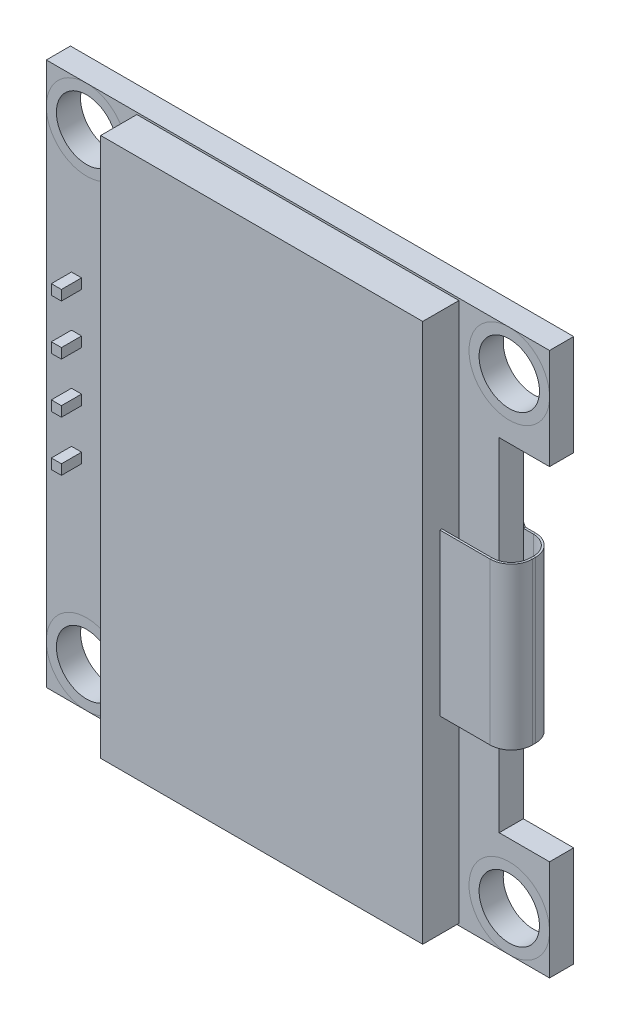
SolidWorks part; units mm, degrees
ref_plane "Front Plane" through (0, 0, 0) normal (0, 0, 1) x (1, 0, 0)
ref_plane "Top Plane" through (0, 0, 0) normal (0, 1, 0) x (1, 0, 0)
ref_plane "Right Plane" through (0, 0, 0) normal (1, 0, 0) x (0, 0, -1)
sketch "Sketch1" plane through (0, 0, 0) normal (0, 0, 1) x (1, 0, 0)
  line L0 (10, -8.5) -> (10, 8.5)
  line L1 (-12.5, -13.5) -> (12.5, -13.5)
  line L2 (-12.5, -13.5) -> (-12.5, 13.5)
  line L3 (-12.5, 13.5) -> (12.5, 13.5)
  line L4 (12.5, -13.5) -> (12.5, 13.5)
  line L5 (12.5, 13.5) -> (10, 13.5)
  line L6 (12.5, 13.5) -> (12.5, 8.5)
  line L7 (12.5, 8.5) -> (10, 8.5)
  line L8 (10, 13.5) -> (10, 8.5)
  line L9 (12.5, -13.5) -> (10, -13.5)
  line L10 (12.5, -13.5) -> (12.5, -8.5)
  line L11 (12.5, -8.5) -> (10, -8.5)
  line L12 (10, -13.5) -> (10, -8.5)
  dimension "D1" = 25
  dimension "D2" = 12.5
  dimension "D3" = 27
  dimension "D4" = 13.5
  dimension "D5" = 5
  dimension "D6" = 2.5
  dimension "D7" = 2.5
  dimension "D8" = 5
extrude "Boss-Extrude1" add sketch "Sketch1" along normal blind 1.2 contours L1 L12 L11 L4 L7 L8 L3 L2
sketch "Sketch2" plane through (0, 0, 1.2) normal (0, 0, 1) x (1, 0, 0)
  line L0 (12.5, 13.5) -> (12.5, 8.5) construction
  line L1 (-12.5, 13.5) -> (12.5, 13.5) construction
  line L2 (-1000, 0) -> (49000, 0) construction
  line L3 (0, -1000) -> (0, 49000) construction
  circle A0 centre (10.5, 11.5) radius 1.5
  circle A1 centre (10.5, -11.5) radius 1.5
  circle A2 centre (-10.5, 11.5) radius 1.5
  circle A3 centre (-10.5, -11.5) radius 1.5
  dimension "D1" = 3
  dimension "D2" = 2
  dimension "D3" = 2
extrude "Cut-Extrude1" cut sketch "Sketch2" against normal through all
sketch "Sketch3" plane through (0, 0, 1.2) normal (0, 0, 1) x (1, 0, 0)
  circle A0 centre (-10.5, 11.5) radius 2
  circle A1 centre (10.5, 11.5) radius 2
  circle A2 centre (10.5, -11.5) radius 2
  circle A3 centre (-10.5, -11.5) radius 2
split line "Split Line1"
sketch "Sketch5" plane through (0, 0, 0) normal (0, 0, -1) x (-1, 0, 0)
  line L0 (12.5, -11.5) -> (12.5, 11.5) construction
  line L1 (12.05, 6) -> (9.95, 6)
  line L2 (12.25, 5.8) -> (12.25, 3.7)
  line L4 (9.75, 5.8) -> (9.75, 3.7)
  line L5 (10.5, 13.5) -> (-10.5, 13.5) construction
  line L6 (12.25, 3.3) -> (12.25, 1.2)
  line L8 (9.75, 3.3) -> (9.75, 1.2)
  line L10 (12.25, 0.8) -> (12.25, -1.3)
  line L12 (9.75, 0.8) -> (9.75, -1.3)
  line L14 (12.25, -1.7) -> (12.25, -3.8)
  line L16 (9.75, -1.7) -> (9.75, -3.8)
  line L17 (12.05, -4) -> (9.95, -4)
  line L18 (12.05, 3.5) -> (9.95, 3.5) [skipped]
  line L19 (12.05, 1) -> (9.95, 1) [skipped]
  line L20 (12.05, -1.5) -> (9.95, -1.5) [skipped]
  arc A0 (9.95, 3.5) -> (9.75, 3.7) centre (9.95, 3.7) cw
  arc A1 (12.25, 3.7) -> (12.05, 3.5) centre (12.05, 3.7) cw
  arc A2 (12.05, 6) -> (12.25, 5.8) centre (12.05, 5.8) cw
  arc A3 (9.95, 6) -> (9.75, 5.8) centre (9.95, 5.8) ccw
  arc A4 (12.05, 3.5) -> (12.25, 3.3) centre (12.05, 3.3) cw
  arc A5 (12.25, 1.2) -> (12.05, 1) centre (12.05, 1.2) cw
  arc A6 (9.95, 3.5) -> (9.75, 3.3) centre (9.95, 3.3) ccw
  arc A7 (9.95, 1) -> (9.75, 1.2) centre (9.95, 1.2) cw
  arc A8 (12.05, 1) -> (12.25, 0.8) centre (12.05, 0.8) cw
  arc A9 (12.25, -1.3) -> (12.05, -1.5) centre (12.05, -1.3) cw
  arc A10 (9.95, 1) -> (9.75, 0.8) centre (9.95, 0.8) ccw
  arc A11 (9.95, -1.5) -> (9.75, -1.3) centre (9.95, -1.3) cw
  arc A12 (12.05, -1.5) -> (12.25, -1.7) centre (12.05, -1.7) cw
  arc A13 (12.25, -3.8) -> (12.05, -4) centre (12.05, -3.8) cw
  arc A14 (9.95, -1.5) -> (9.75, -1.7) centre (9.95, -1.7) ccw
  arc A15 (9.95, -4) -> (9.75, -3.8) centre (9.95, -3.8) cw
  point P12 (12.25, 3.5)
  point P15 (12.25, 6)
  point P18 (9.75, 6)
  dimension "D5" = 0.2
  dimension "D1" = 2.5
  dimension "D2" = 2.5
  dimension "D3" = 0.25
  dimension "D4" = 7.5
  dimension "D6" = 4
extrude "Boss-Extrude2" add sketch "Sketch5" along normal blind 2.5
sketch "Sketch6" plane through (0, 0, -2.5) normal (0, 0, -1) x (-1, 0, 0)
  line L0 (9.75, 5.8) -> (9.75, 3.7) construction
  line L1 (10.75, 5) -> (11.25, 5)
  line L2 (10.75, 5) -> (10.75, 4.5)
  line L3 (10.75, 4.5) -> (11.25, 4.5)
  line L4 (11.25, 5) -> (11.25, 4.5)
  line L5 (12.05, 6) -> (9.95, 6) construction
  line L6 (10.75, 2.5) -> (10.75, 2)
  line L7 (10.75, 2.5) -> (11.25, 2.5)
  line L8 (11.25, 2.5) -> (11.25, 2)
  line L9 (10.75, 2) -> (11.25, 2)
  line L10 (10.75, 0) -> (10.75, -0.5)
  line L11 (10.75, 0) -> (11.25, 0)
  line L12 (11.25, 0) -> (11.25, -0.5)
  line L13 (10.75, -0.5) -> (11.25, -0.5)
  line L14 (10.75, -2.5) -> (10.75, -3)
  line L15 (10.75, -2.5) -> (11.25, -2.5)
  line L16 (11.25, -2.5) -> (11.25, -3)
  line L17 (10.75, -3) -> (11.25, -3)
  dimension "D1" = 0.5
  dimension "D2" = 0.5
  dimension "D3" = 1
  dimension "D4" = 1
  dimension "D5" = 4
extrude "Boss-Extrude3" add sketch "Sketch6" along normal blind 5.5 and the other way blind 4.7
sketch "Sketch7" plane through (0, 0, 1.2) normal (0, 0, 1) x (1, 0, 0)
  line L0 (-10.5, 13.5) -> (10.5, 13.5) construction
  line L1 (-8, -13.4) -> (8, -13.4)
  line L2 (-8, -13.4) -> (-8, 13.4)
  line L3 (-8, 13.4) -> (8, 13.4)
  line L4 (8, -13.4) -> (8, 13.4)
  line L5 (-10.5, -13.5) -> (10.5, -13.5) construction
  line L6 (-12.5, -11.5) -> (-12.5, 11.5) construction
  dimension "D1" = 16
  dimension "D2" = 0.1
  dimension "D3" = 0.1
  dimension "D4" = 4.5
extrude "Boss-Extrude4" add sketch "Sketch7" along normal blind 1.8
sketch "Sketch8" plane through (0, 0, 0) normal (0, 0, -1) x (-1, 0, 0)
  line L0 (10.5, 13.5) -> (-10.5, 13.5) construction
  line L1 (0, 12.5) -> (1.5, 12.5)
  line L2 (0, 12.5) -> (0, 11.75)
  line L3 (0, 11.75) -> (1.5, 11.75)
  line L4 (1.5, 12.5) -> (1.5, 11.75)
  line L5 (-12.5, 13.5) -> (-12.5, 11.5) construction
  line L6 (0, 9.7778) -> (0, 9.0278)
  line L7 (0, 9.7778) -> (1.5, 9.7778)
  line L8 (1.5, 9.7778) -> (1.5, 9.0278)
  line L9 (0, 9.0278) -> (1.5, 9.0278)
  line L10 (0, 7.0556) -> (0, 6.3056)
  line L11 (0, 7.0556) -> (1.5, 7.0556)
  line L12 (1.5, 7.0556) -> (1.5, 6.3056)
  line L13 (0, 6.3056) -> (1.5, 6.3056)
  line L14 (0, 4.3333) -> (0, 3.5833)
  line L15 (0, 4.3333) -> (1.5, 4.3333)
  line L16 (1.5, 4.3333) -> (1.5, 3.5833)
  line L17 (0, 3.5833) -> (1.5, 3.5833)
  line L18 (0, 1.6111) -> (0, 0.8611)
  line L19 (0, 1.6111) -> (1.5, 1.6111)
  line L20 (1.5, 1.6111) -> (1.5, 0.8611)
  line L21 (0, 0.8611) -> (1.5, 0.8611)
  line L22 (0, -1.1111) -> (0, -1.8611)
  line L23 (0, -1.1111) -> (1.5, -1.1111)
  line L24 (1.5, -1.1111) -> (1.5, -1.8611)
  line L25 (0, -1.8611) -> (1.5, -1.8611)
  line L26 (0, -3.8333) -> (0, -4.5833)
  line L27 (0, -3.8333) -> (1.5, -3.8333)
  line L28 (1.5, -3.8333) -> (1.5, -4.5833)
  line L29 (0, -4.5833) -> (1.5, -4.5833)
  line L30 (0, -6.5556) -> (0, -7.3056)
  line L31 (0, -6.5556) -> (1.5, -6.5556)
  line L32 (1.5, -6.5556) -> (1.5, -7.3056)
  line L33 (0, -7.3056) -> (1.5, -7.3056)
  line L34 (0, -9.2778) -> (0, -10.0278)
  line L35 (0, -9.2778) -> (1.5, -9.2778)
  line L36 (1.5, -9.2778) -> (1.5, -10.0278)
  line L37 (0, -10.0278) -> (1.5, -10.0278)
  line L38 (0, -12) -> (0, -12.75)
  line L39 (0, -12) -> (1.5, -12)
  line L40 (1.5, -12) -> (1.5, -12.75)
  line L41 (0, -12.75) -> (1.5, -12.75)
  line L42 (10.5, -13.5) -> (-10.5, -13.5) construction
  line L43 (-1000, 0) -> (49000, 0) construction
  line L44 (-2, -9) -> (-2.75, -9)
  line L45 (-2, -9) -> (-2, -10.5)
  line L46 (-2, -10.5) -> (-2.75, -10.5)
  line L47 (-2.75, -9) -> (-2.75, -10.5)
  line L48 (-3.75, -10.5) -> (-4.5, -10.5)
  line L49 (-3.75, -10.5) -> (-3.75, -9)
  line L50 (-3.75, -9) -> (-4.5, -9)
  line L51 (-4.5, -10.5) -> (-4.5, -9)
  line L52 (-2, 10.5) -> (-2.75, 10.5)
  line L53 (-2.75, 9) -> (-2.75, 10.5)
  line L54 (-2, 9) -> (-2.75, 9)
  line L55 (-2, 9) -> (-2, 10.5)
  line L56 (-3.75, 9) -> (-4.5, 9)
  line L57 (-4.5, 10.5) -> (-4.5, 9)
  line L58 (-3.75, 10.5) -> (-4.5, 10.5)
  line L59 (-3.75, 10.5) -> (-3.75, 9)
  point P54 (-3.75, -9.75)
  dimension "D1" = 0.75
  dimension "D2" = 1
  dimension "D3" = 1.5
  dimension "D4" = 12.5
  dimension "D6" = 0.75
  dimension "D7" = 0.75
  dimension "D8" = 1.5
  dimension "D9" = 0.75
  dimension "D10" = 1.5
  dimension "D11" = 2
  dimension "D12" = 1
  dimension "D13" = 3
  dimension "D5" = 10
extrude "Boss-Extrude5" add sketch "Sketch8" along normal blind 0.8
sketch "Sketch9" plane through (0, 13.5, 0) normal (0, 1, 0) x (1, 0, 0)
  line L0 (8, -2.1) -> (10.5, -2.1)
  line L1 (8, -3) -> (8, -1.2) construction
  line L2 (11.5, -1.1) -> (11.5, -0.95)
  line L3 (10.5, 0.05) -> (9, 0.05)
  line L4 (9, 0.05) -> (11.5, -1.1)
  line L5 (12.5, -1.2) -> (12.5, 0) construction
  line L6 (-10.5, 0) -> (10.5, 0) construction
  arc A0 (10.5, -2.1) -> (11.5, -1.1) centre (10.5, -1.1) ccw
  arc A1 (11.5, -0.95) -> (10.5, 0.05) centre (10.5, -0.95) ccw
  point P12 (12.5, -0.6)
  dimension "D1" = 1
  dimension "D4" = 0.05
  dimension "D2" = 3.5
  dimension "D3" = 1
sketch "Sketch10" plane through (8, 0, 0) normal (1, 0, 0) x (0, 0, -1)
  line L1 (-2.15, -4) -> (-2.05, -4)
  line L2 (-2.15, -4) -> (-2.15, 4)
  line L3 (-2.15, 4) -> (-2.05, 4)
  line L4 (-2.05, -4) -> (-2.05, 4)
  line L5 (-2.1, -986.5) -> (-2.1, 49013.5) construction
  line L7 (-3, -13.4) -> (-3, 13.4) construction
  dimension "D1" = 0.05
  dimension "D2" = 0.9
  dimension "D3" = 0.1
  dimension "D4" = 8
  dimension "D5" = 4
sweep "Sweep1" add profiles "Sketch10" path "Sketch9"
sketch "Sketch11" plane through (0, 0, 0) normal (0, 0, -1) x (-1, 0, 0)
  line L0 (-6.5, -11.1) -> (-6.5, 11.1)
  line L1 (-12.5, 11.5) -> (-12.5, 8.5) construction
  line L4 (-10, 4) -> (-9, 4) construction
  line L5 (-10, -4) -> (-9, -4) construction
  line L6 (-9, -4) -> (-9, 4) construction
  line L7 (-10, -4) -> (-9, -4)
  line L8 (-10, 4) -> (-9, 4)
  line L9 (-9, -4) -> (-9, 4)
  line L10 (-10, 4) -> (-6.5724, 11.1)
  line L11 (-10, -4) -> (-6.5724, -11.1)
  line L12 (-6.5724, -11.1) -> (-6.5, -11.1)
  line L13 (-6.5724, 11.1) -> (-6.5, 11.1)
  point P14 (-6.5362, 11.1)
  dimension "D1" = 6
  dimension "D2" = 22.2
  dimension "D3" = 0.0724
extrude "Boss-Extrude6" add sketch "Sketch11" along normal blind 0.1
sketch "Sketch12" plane through (0, 0, 0) normal (0, 0, -1) x (-1, 0, 0)
  line L0 (-6.5724, -11.1) -> (-6.5, -11.1) construction
  line L1 (-6.5, 11.1) -> (-5.5, 11.1)
  line L2 (-6.5, 11.1) -> (-6.5, -11.1)
  line L3 (-6.5, -11.1) -> (-5.5, -11.1)
  line L4 (-5.5, 11.1) -> (-5.5, -11.1)
  dimension "D1" = 1
extrude "Boss-Extrude7" add sketch "Sketch12" along normal blind 0.06
